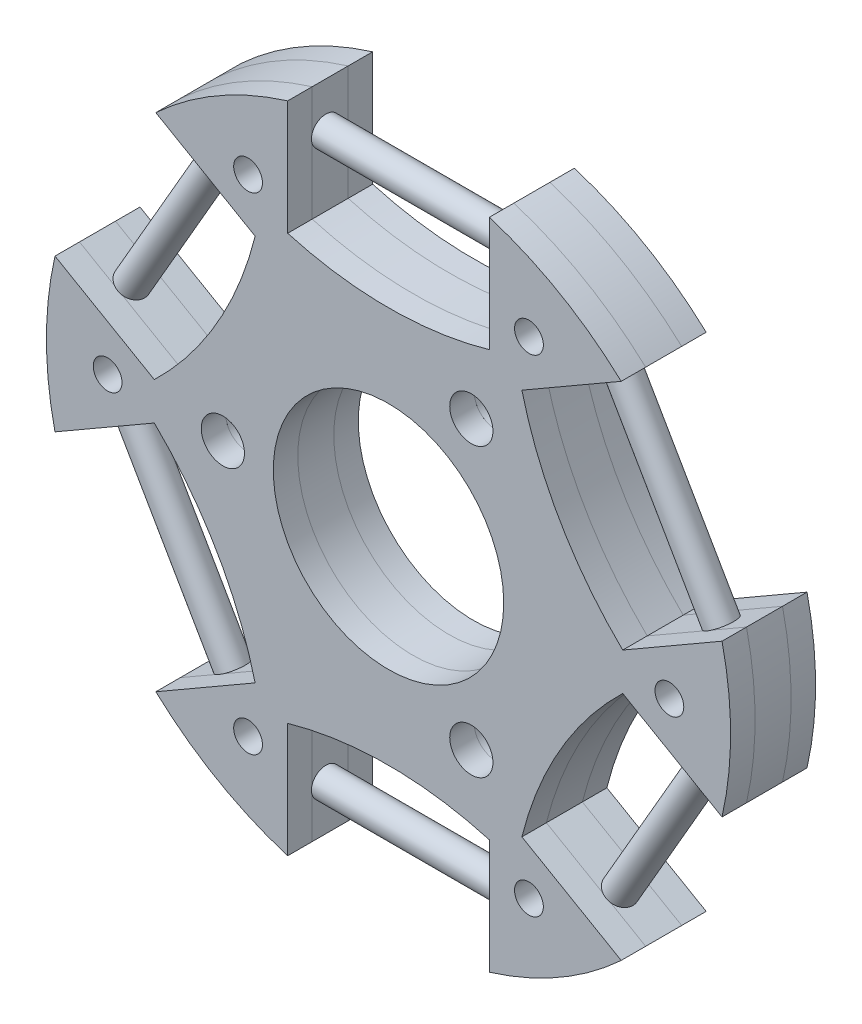
SolidWorks part; units mm, degrees
material "AISI 304"
ref_plane "前视基准面" through (0, 0, 0) normal (0, 0, 1) x (1, 0, 0)
ref_plane "上视基准面" through (0, 0, 0) normal (0, 1, 0) x (1, 0, 0)
ref_plane "右视基准面" through (0, 0, 0) normal (1, 0, 0) x (0, 0, -1)
sketch "草图1" plane through (0, 0, 0) normal (0, 0, 1) x (1, 0, 0)
  circle A0 centre (0, 0) radius 25.4
  circle A1 centre (0, 0) radius 8
  dimension "D1" = 50.8
  dimension "D2" = 16
extrude "凸台-拉伸1" add sketch "草图1" along normal blind 1.7
sketch "草图2" plane through (0, 0, 1.7) normal (0, 0, 1) x (1, 0, 0)
  circle A0 centre (0, 0) radius 25.4
  circle A1 centre (0, 0) radius 3.5
  dimension "D1" = 7
extrude "凸台-拉伸2" add sketch "草图2" along normal blind 2.5 separate body
sketch "草图3" plane through (0, 0, 4.2) normal (0, 0, 1) x (1, 0, 0)
  circle A0 centre (0, 0) radius 25.4
  circle A1 centre (0, 0) radius 8
  dimension "D1" = 16
extrude "凸台-拉伸3" add sketch "草图3" along normal blind 1.7 separate body
sketch "草图4" plane through (0, 0, 5.9) normal (0, 0, 1) x (1, 0, 0)
  line L0 (9.2597, 13.429) -> (17.6452, 18.2704)
  line L1 (7, 14.7336) -> (7, 24.4164)
  line L2 (-7, 14.7336) -> (-7, 24.4164)
  line L3 (16.2597, 1.3046) -> (24.6452, 6.146)
  line L4 (16.2597, -1.3046) -> (24.6452, -6.146)
  line L5 (9.2597, -13.429) -> (17.6452, -18.2704)
  line L6 (7, -14.7336) -> (7, -24.4164)
  line L7 (-7, -14.7336) -> (-7, -24.4164)
  line L8 (-9.2597, -13.429) -> (-17.6452, -18.2704)
  line L9 (-16.2597, -1.3046) -> (-24.6452, -6.146)
  line L10 (-16.2597, 1.3046) -> (-24.6452, 6.146)
  line L11 (-9.2597, 13.429) -> (-17.6452, 18.2704)
  arc A0 (7, 24.4164) -> (-7, 24.4164) centre (0, 0) ccw
  arc A1 (9.2597, 13.429) -> (16.2597, 1.3046) centre (33.9049, 19.575) ccw
  arc A2 (-7, 14.7336) -> (7, 14.7336) centre (0, 39.15) ccw
  arc A3 (24.6452, 6.146) -> (17.6452, 18.2704) centre (0, 0) ccw
  arc A4 (16.2597, -1.3046) -> (9.2597, -13.429) centre (33.9049, -19.575) ccw
  arc A5 (17.6452, -18.2704) -> (24.6452, -6.146) centre (0, 0) ccw
  arc A6 (7, -14.7336) -> (-7, -14.7336) centre (0, -39.15) ccw
  arc A7 (-7, -24.4164) -> (7, -24.4164) centre (0, 0) ccw
  arc A8 (-9.2597, -13.429) -> (-16.2597, -1.3046) centre (-33.9049, -19.575) ccw
  arc A9 (-24.6452, -6.146) -> (-17.6452, -18.2704) centre (0, 0) ccw
  arc A10 (-16.2597, 1.3046) -> (-9.2597, 13.429) centre (-33.9049, 19.575) ccw
  arc A11 (-17.6452, 18.2704) -> (-24.6452, 6.146) centre (0, 0) ccw
  point P34 (0, 0)
  dimension "D1" = 50.8
  dimension "D2" = 6
  dimension "D3" = 50.8
extrude "切除-拉伸1" cut sketch "草图4" against normal blind 20.5
sketch "草图5" plane through (0, 0, 5.9) normal (0, 0, 1) x (1, 0, 0)
  circle A2 centre (9.75, 16.8875) radius 1
  circle A3 centre (19.5, 0) radius 1
  circle A4 centre (9.75, -16.8875) radius 1
  circle A5 centre (-9.75, -16.8875) radius 1
  circle A6 centre (-19.5, 0) radius 1
  circle A7 centre (-9.75, 16.8875) radius 1
  point P21 (0, 0)
  dimension "D2" = 2
  dimension "D3" = 6
extrude "切除-拉伸2" cut sketch "草图5" against normal blind 20.5
sketch "草图6" plane through (-7, 0, 0) normal (1, 0, 0) x (0, 0, -1)
  circle A0 centre (-3.25, 19.575) radius 1
  dimension "D1" = 2
extrude "凸台-拉伸4" add sketch "草图6" along normal blind 14
pattern_circular "阵列(圆周)1" count 6 over 360 about axis through (0, 0, 0) along (0, 0, 1) of "凸台-拉伸4"
sketch "草图7" plane through (0, 0, 4.2) normal (0, 0, 1) x (1, 0, 0)
  circle A1 centre (-7, 0) radius 1
  circle A2 centre (0, 7) radius 1
  circle A3 centre (7, 0) radius 1
  circle A4 centre (0, -7) radius 1
  point P14 (0, 0)
  dimension "D2" = 2
  dimension "D3" = 4
extrude "切除-拉伸3" cut sketch "草图7" against normal blind 14
sketch "草图8" plane through (0, 0, 5.9) normal (0, 0, 1) x (1, 0, 0)
  circle A0 centre (0, 0) radius 23.75
  circle A1 centre (0, 0) radius 25.4
  dimension "D1" = 47.5
extrude "切除-拉伸4" cut sketch "草图8" against normal blind 10
sketch "草图9" plane through (0, 0, 5.9) normal (0, 0, 1) x (1, 0, 0)
  circle A0 centre (0, 0) radius 8
  dimension "D1" = 16
extrude "切除-拉伸5" cut sketch "草图9" against normal through all
sketch "草图10" plane through (0, 0, 0) normal (0, 0, -1) x (-1, 0, 0)
  line L0 (0, 11.5) -> (0, 0) construction
  line L1 (0, 0) -> (-5.75, 9.9593) construction
  circle A0 centre (0, 0) radius 11.5 construction
  circle A1 centre (-5.75, 9.9593) radius 1.5
  circle A2 centre (11.5, 0) radius 1.5
  circle A3 centre (-5.75, -9.9593) radius 1.5
  point P6 (0, -9.6832)
  point P7 (0, 0)
  point P12 (0, 0)
  dimension "D1" = 23
  dimension "D2" = 3
  dimension "D3" = 30
  dimension "D4" = 3
extrude "切除-拉伸6" cut sketch "草图10" against normal through all
